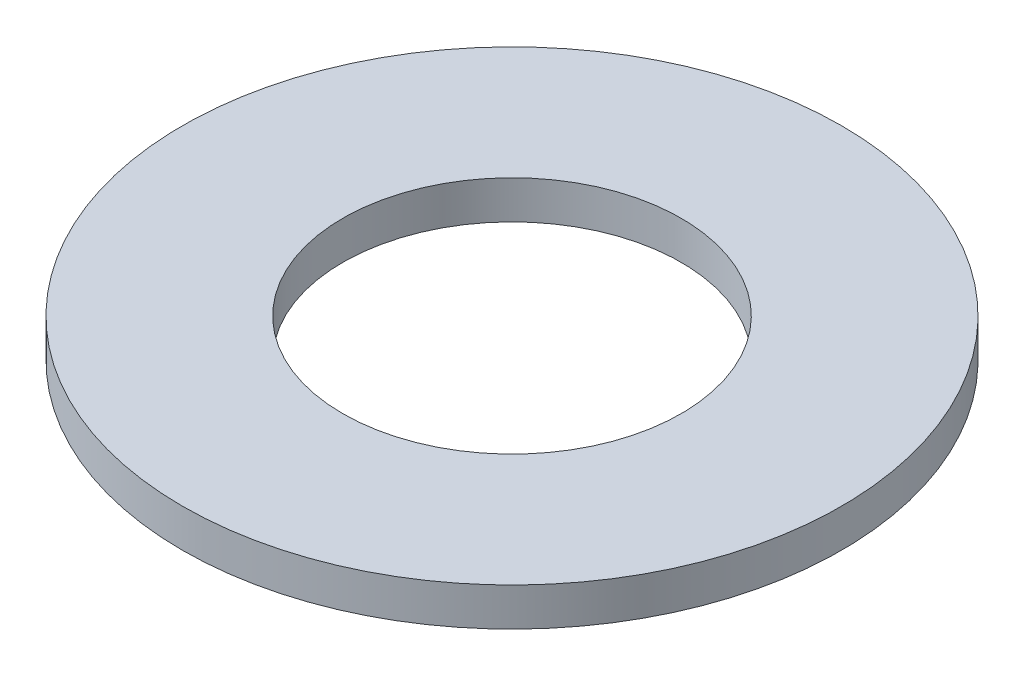
SolidWorks part; units mm, degrees
material "ASTM A36 Steel"
ref_plane "Front Plane" through (0, 0, 0) normal (0, 0, 1) x (1, 0, 0)
ref_plane "Top Plane" through (0, 0, 0) normal (0, 1, 0) x (1, 0, 0)
ref_plane "Right Plane" through (0, 0, 0) normal (1, 0, 0) x (0, 0, -1)
sketch "Sketch1" plane through (0, 0, 0) normal (0, 1, 0) x (1, 0, 0)
  circle A1 centre (0, 0) radius 4.3815
  dimension "D1" = 8.763
extrude "Boss-Extrude1" add sketch "Sketch1" along normal blind 0.508
hole_wizard "M4 Clearance Hole1" positions "Sketch2" profile "Sketch4" hole size "M4" standard "ANSI Metric" end condition through all
sketch "Sketch2" plane through (0, 0.508, 0) normal (0, 1, 0) x (1, 0, 0)
  point P0 (0, 0)
sketch "Sketch4" plane through (0, 0.508, 0) normal (1, 0, 0) x (0, 0, 1)
  line L0 (0, 0) -> (0, 0.508)
  line L1 (0, 0.508) -> (2.25, 0.508)
  line L2 (2.25, 0.508) -> (2.25, 0)
  line L5 (2.25, 0) -> (0, 0)
  line L11 (0, -6.35) -> (0, 107.95) construction
  dimension "Thru Hole Dia." = 4.5
  dimension "Thru Hole Depth" = 0.508
